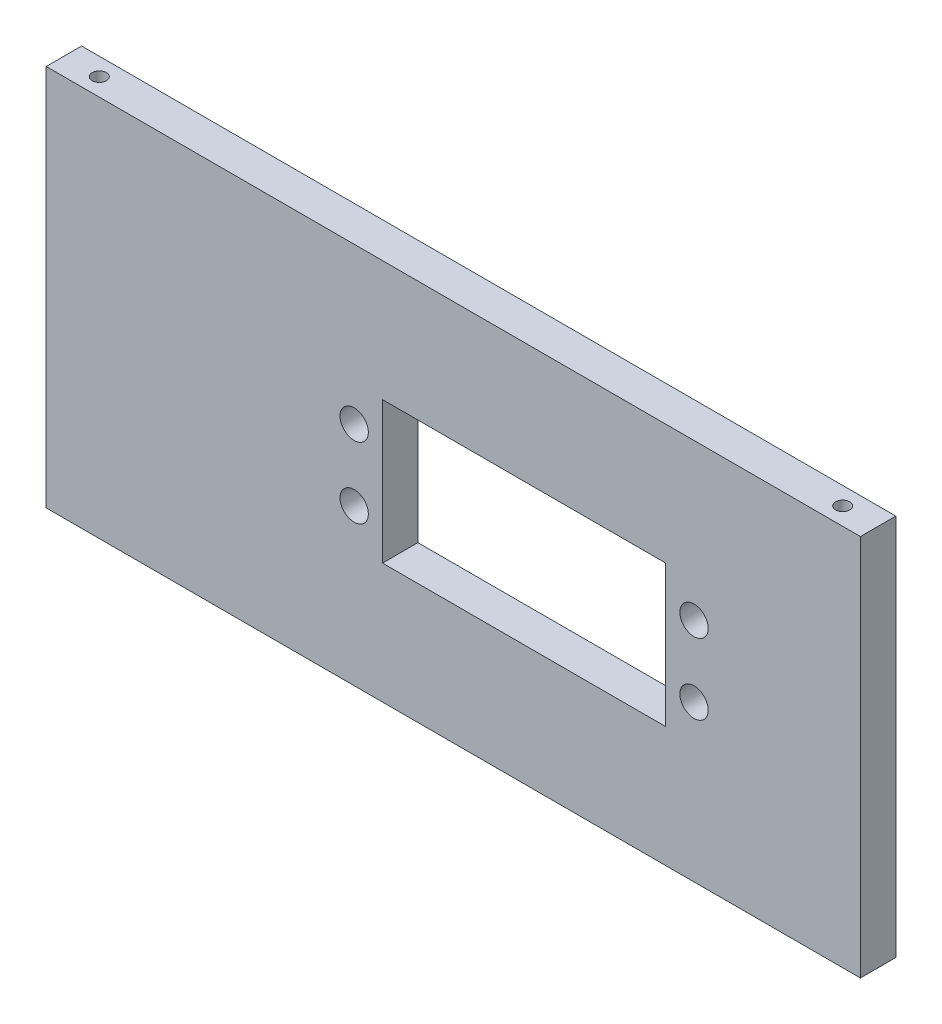
SolidWorks part; units mm, degrees
ref_plane "前基準面" through (0, 0, 0) normal (0, 0, 1) x (1, 0, 0)
ref_plane "上基準面" through (0, 0, 0) normal (0, 1, 0) x (1, 0, 0)
ref_plane "右基準面" through (0, 0, 0) normal (1, 0, 0) x (0, 0, -1)
sketch "草圖1" plane through (0, 0, 0) normal (0, 0, 1) x (1, 0, 0)
  line L1 (-44.4375, 23.5159) -> (70.5625, 23.5159)
  line L2 (-44.4375, 23.5159) -> (-44.4375, -30.4841)
  line L3 (-44.4375, -30.4841) -> (70.5625, -30.4841)
  line L4 (70.5625, 23.5159) -> (70.5625, -30.4841)
  line L5 (13.0625, -30.4841) -> (13.0625, 23.5159) construction
  line L6 (-44.4375, -3.4841) -> (70.5625, -3.4841) construction
  line L7 (3.0625, 6.5159) -> (43.0625, 6.5159)
  line L8 (3.0625, 6.5159) -> (3.0625, -13.4841)
  line L9 (3.0625, -13.4841) -> (43.0625, -13.4841)
  line L10 (43.0625, 6.5159) -> (43.0625, -13.4841)
  line L11 (23.0625, -13.4841) -> (23.0625, 6.5159) construction
  line L12 (3.0625, -3.4841) -> (43.0625, -3.4841) construction
  circle A0 centre (-0.9375, -8.4841) radius 2
  circle A1 centre (47.0625, -8.4841) radius 2
  circle A2 centre (-0.9375, 1.5159) radius 2
  circle A3 centre (47.0625, 1.5159) radius 2
  point P16 (13.0625, -2.6437)
  point P17 (13.0625, -2.2816)
  point P20 (23.6777, 1.4522)
  point P21 (10.6092, -2.2816)
  point P22 (0, 0)
  point P23 (13.0625, -2.7427)
  point P24 (-0.9374, 1.532)
  point P25 (47.0625, 1.5159)
  point P26 (-1.5046, 1.5159)
  point P132 (23.0625, -3.4841)
  point P140 (13.0625, -3.4841)
  dimension "D5" = 4
  dimension "D9" = 4
  dimension "D1" = 115
  dimension "D2" = 54
  dimension "D3" = 20
  dimension "D4" = 40
  dimension "D6" = 48
  dimension "D7" = 4
  dimension "D8" = 10
  dimension "D10" = 5
  dimension "D11" = 5
  dimension "D12" = 10
  dimension "D16" = 48
extrude "填料-伸長3" add sketch "草圖1" along normal blind 5 contours A2 | A1 | A0 | L7 L10 L9 L8 | L1 L4 L3 L2 | A3
sketch "草圖2" plane through (0, 23.5159, 0) normal (0, 1, 0) x (1, 0, 0)
  line L0 (-44.4375, -5) -> (70.5625, -5) construction
  line L1 (70.5625, -5) -> (70.5625, 0) construction
  circle A0 centre (-39.4375, -2.5) radius 1
  circle A1 centre (65.5625, -2.5) radius 1
  point P6 (-25.984, -2.5)
  point P7 (64.9729, -2.5)
  point P10 (0, 0)
  dimension "D2" = 2
  dimension "D3" = 105
  dimension "D5" = 2
  dimension "D1" = 2.5
  dimension "D4" = 5
extrude "除料-伸長1" cut sketch "草圖2" against normal blind 15 contours A0 | A1
sketch "草圖3" plane through (0, -30.4841, 0) normal (0, -1, 0) x (1, 0, 0)
  line L0 (-44.4375, 5) -> (70.5625, 5) construction
  line L1 (70.5625, 5) -> (70.5625, 0) construction
  circle A0 centre (29.0625, 2.5) radius 1.75
  circle A1 centre (-2.9375, 2.5) radius 1.75
  point P6 (27.7505, 2.5)
  dimension "D1" = 3.5
  dimension "D2" = 2.5
  dimension "D3" = 32
  dimension "D4" = 41.5
extrude "除料-伸長2" cut sketch "草圖3" against normal blind 15 contours A1 | A0
